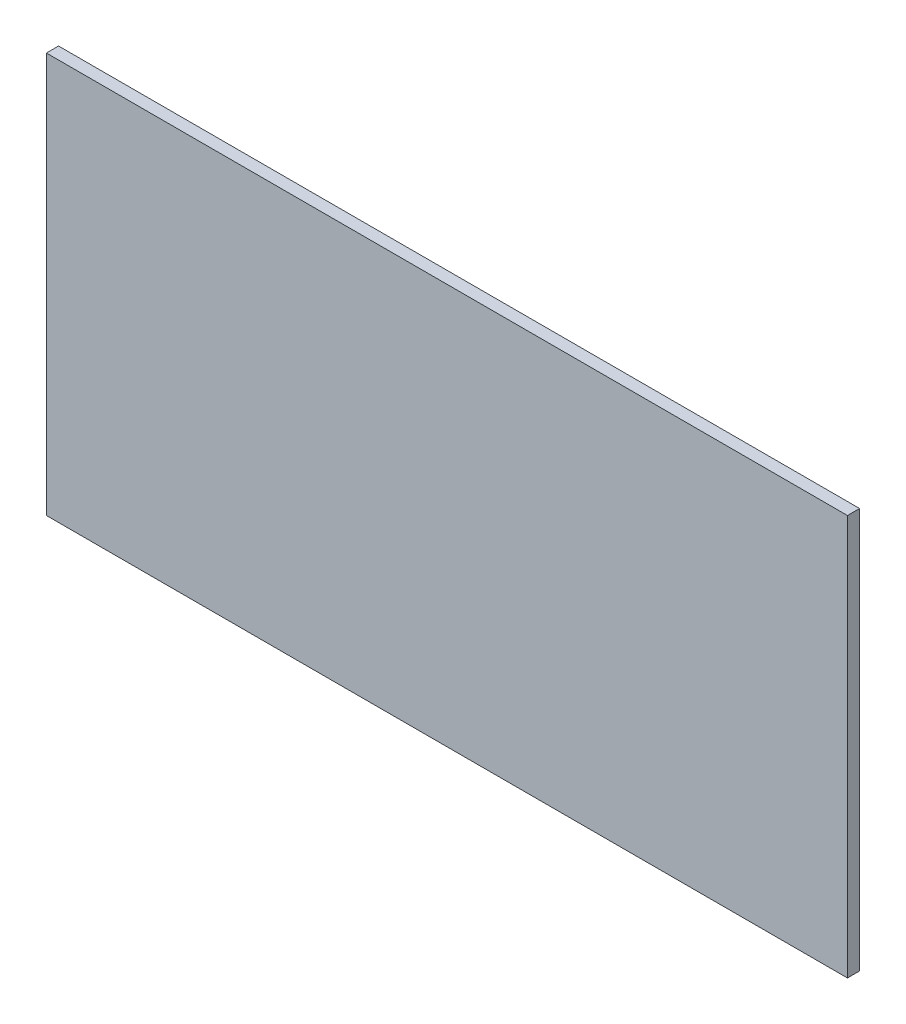
SolidWorks part; units mm, degrees
ref_plane "前视基准面" through (0, 0, 0) normal (0, 0, 1) x (1, 0, 0)
ref_plane "上视基准面" through (0, 0, 0) normal (0, 1, 0) x (1, 0, 0)
ref_plane "右视基准面" through (0, 0, 0) normal (1, 0, 0) x (0, 0, -1)
other "Configuration Table"
sketch "草图1" plane through (0, 0, 0) normal (0, 0, 1) x (1, 0, 0)
  line L1 (-35.3121, 38.077) -> (96.6879, 38.077)
  line L2 (-35.3121, 38.077) -> (-35.3121, -27.923)
  line L3 (-35.3121, -27.923) -> (96.6879, -27.923)
  line L4 (96.6879, 38.077) -> (96.6879, -27.923)
  dimension "D1" = 66
  dimension "D2" = 132
extrude "凸台-拉伸1" add sketch "草图1" along normal blind 2
